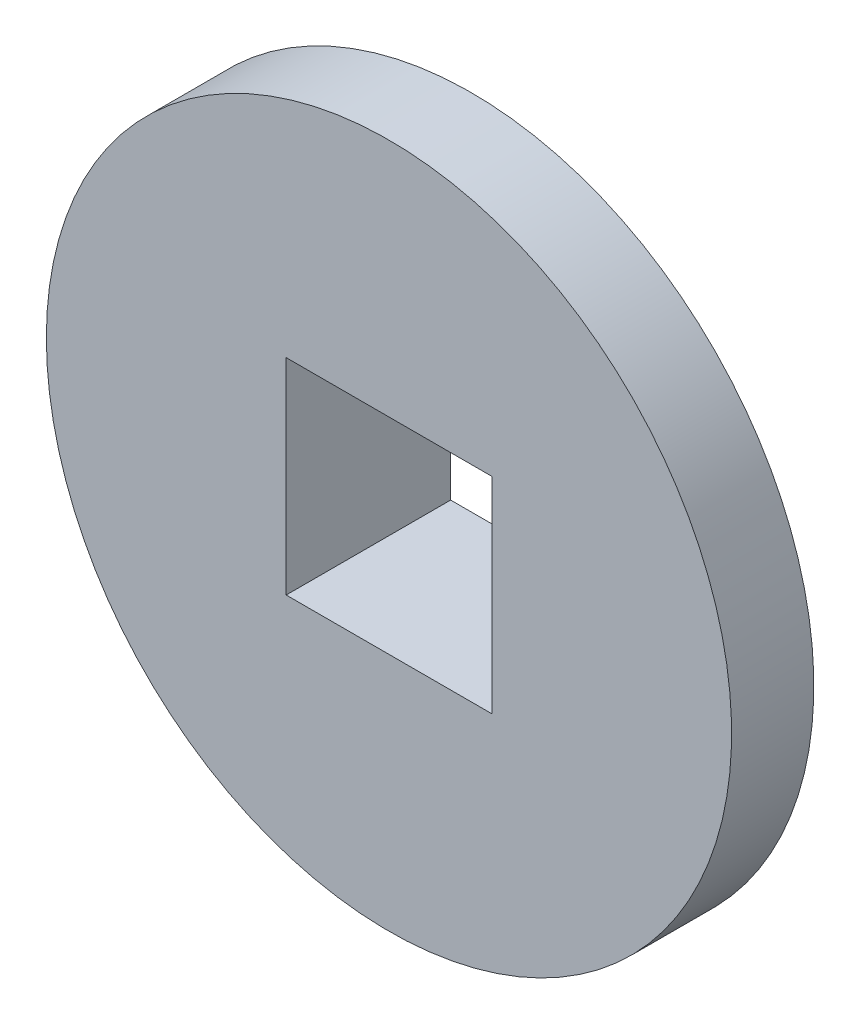
SolidWorks part; units mm, degrees
ref_plane "Front Plane" through (0, 0, 0) normal (0, 0, 1) x (1, 0, 0)
ref_plane "Top Plane" through (0, 0, 0) normal (0, 1, 0) x (1, 0, 0)
ref_plane "Right Plane" through (0, 0, 0) normal (1, 0, 0) x (0, 0, -1)
sketch "Sketch1" plane through (0, 0, 0) normal (0, 0, 1) x (1, 0, 0)
  circle A0 centre (-130.2016, 15.0776) radius 15.875
extrude "Boss-Extrude1" add sketch "Sketch1" along normal blind 3.81
sketch "Sketch2" plane through (0, 0, 0) normal (0, 0, -1) x (-1, 0, 0)
  circle A0 centre (130.2016, 15.0776) radius 9.144
  dimension "D1" = 18.288
extrude "Boss-Extrude2" add sketch "Sketch2" along normal blind 3.81
sketch "Sketch3" plane through (0, 0, -3.81) normal (0, 0, -1) x (-1, 0, 0)
  line L1 (125.4391, 10.3151) -> (134.9641, 10.3151)
  line L2 (125.4391, 10.3151) -> (125.4391, 19.8401)
  line L3 (125.4391, 19.8401) -> (134.9641, 19.8401)
  line L4 (134.9641, 10.3151) -> (134.9641, 19.8401)
  line L5 (125.4391, 10.3151) -> (134.9641, 19.8401) construction
  line L6 (125.4391, 19.8401) -> (134.9641, 10.3151) construction
  point P0 (130.2016, 15.0776)
  dimension "D1" = 9.525
  dimension "D2" = 9.525
extrude "Cut-Extrude1" cut sketch "Sketch3" against normal blind 9.652
